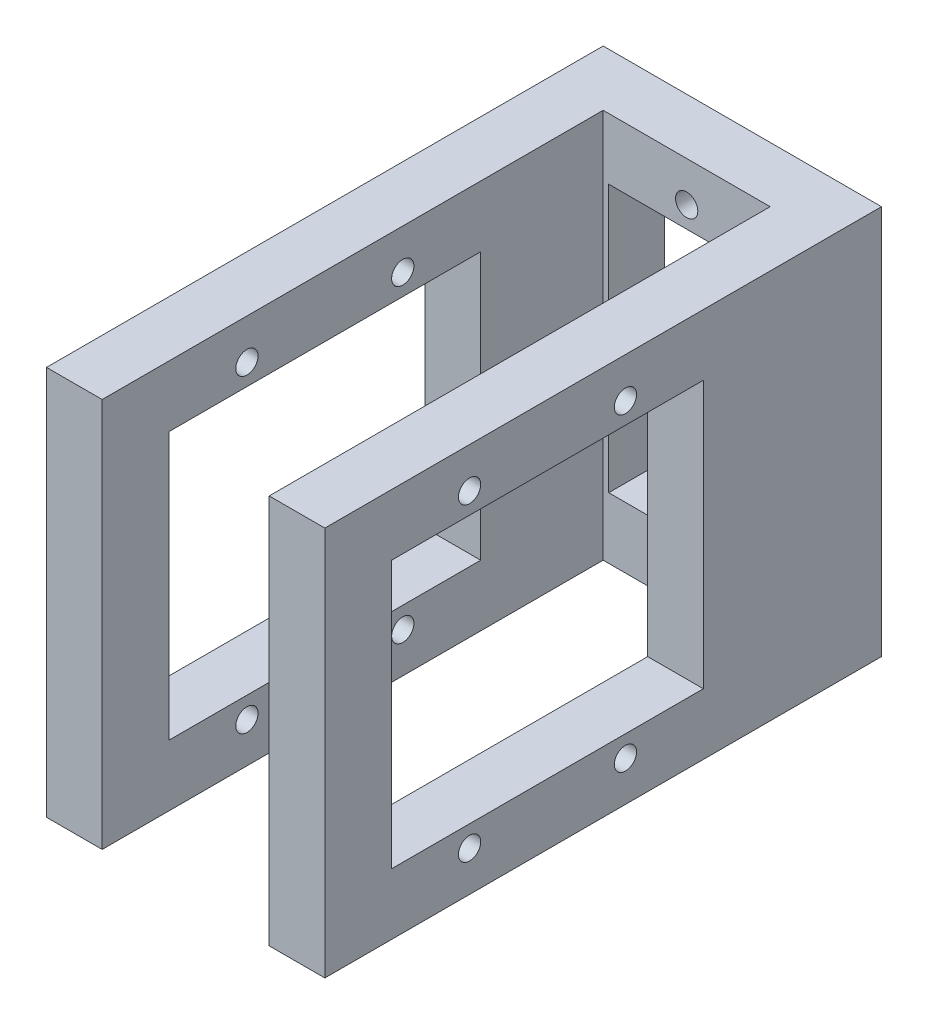
SolidWorks part; units mm, degrees
ref_plane "前视基准面" through (0, 0, 0) normal (0, 0, 1) x (1, 0, 0)
ref_plane "上视基准面" through (0, 0, 0) normal (0, 1, 0) x (1, 0, 0)
ref_plane "右视基准面" through (0, 0, 0) normal (1, 0, 0) x (0, 0, -1)
other "Configuration Table"
sketch "Sketch1" plane through (0, 0, 0) normal (0, 0, 1) x (1, 0, 0)
  line L0 (0, 0) -> (0, 13.9) construction
  line L1 (-10, -17.5) -> (10, -17.5)
  line L2 (-10, -17.5) -> (-10, 17.5)
  line L3 (-10, 17.5) -> (10, 17.5)
  line L4 (10, -17.5) -> (10, 17.5)
  line L5 (-10, -17.5) -> (10, 17.5) construction
  line L6 (-10, 17.5) -> (10, -17.5) construction
  line L7 (-7, -12) -> (7, -12)
  line L8 (-7, -12) -> (-7, 12)
  line L9 (-7, 12) -> (7, 12)
  line L10 (7, -12) -> (7, 12)
  line L11 (-7, -12) -> (7, 12) construction
  line L12 (-7, 12) -> (7, -12) construction
  line L13 (0, 0) -> (10, 0) construction
  circle A0 centre (0, 13.9) radius 1
  circle A1 centre (0, -13.9) radius 1
  point P0 (0, 0)
  point P6 (0, 0)
  dimension "D5" = 2
  dimension "D1" = 20
  dimension "D2" = 35
  dimension "D3" = 14
  dimension "D4" = 24
  dimension "D6" = 13.9
extrude "Boss-Extrude1" add sketch "Sketch1" along normal blind 5
sketch "Sketch2" plane through (10, 0, 0) normal (1, 0, 0) x (0, 0, -1)
  line L1 (0, 17.5) -> (-50, 17.5)
  line L2 (0, 17.5) -> (0, -17.5)
  line L3 (0, -17.5) -> (-50, -17.5)
  line L4 (-50, 17.5) -> (-50, -17.5)
  dimension "D1" = 35
  dimension "D2" = 50
extrude "Boss-Extrude2" add sketch "Sketch2" along normal mid plane 5
sketch "Sketch3" plane through (7.5, 0, 0) normal (-1, 0, 0) x (0, 0, 1)
  line L0 (5, 0) -> (30, 0) construction
  line L1 (30, 12) -> (30, -12) construction
  line L2 (16, -12) -> (44, -12)
  line L3 (5, 17.5) -> (5, -17.5) construction
  line L4 (16, -12) -> (16, 12)
  line L5 (16, 12) -> (44, 12)
  line L6 (44, -12) -> (44, 12)
  line L7 (16, -12) -> (44, 12) construction
  line L8 (16, 12) -> (44, -12) construction
  line L9 (30, 0) -> (23, 0) construction
  line L10 (23, 0) -> (23, 13.9) construction
  circle A0 centre (23, 13.9) radius 1
  circle A3 centre (37, 13.9) radius 1
  circle A4 centre (37, -13.9) radius 1
  circle A5 centre (23, -13.9) radius 1
  dimension "D3" = 2
  dimension "D1" = 28
  dimension "D2" = 24
  dimension "D4" = 13.9
  dimension "D5" = 25
  dimension "D6" = 7
extrude "Cut-Extrude1" cut sketch "Sketch3" against normal blind 5
ref_plane "Plane2" through (0, 0, 0) normal (-1, 0, 0) x (0, 0, 1)
mirror "Mirror2" about plane through (0, 0, 0) normal (-1, 0, 0) of "Cut-Extrude1", "Boss-Extrude2"
